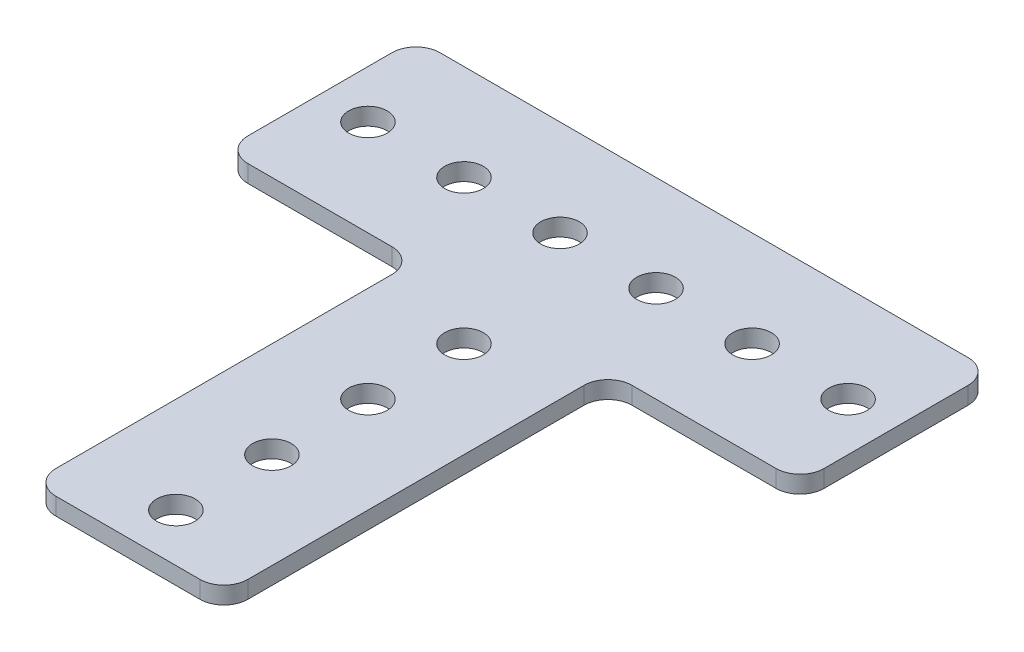
SolidWorks part; units mm, degrees
ref_plane "Front Plane" through (0, 0, 0) normal (0, 0, 1) x (1, 0, 0)
ref_plane "Top Plane" through (0, 0, 0) normal (0, 1, 0) x (1, 0, 0)
ref_plane "Right Plane" through (0, 0, 0) normal (1, 0, 0) x (0, 0, -1)
sketch "Sketch1" plane through (0, 0, 0) normal (0, 1, 0) x (1, 0, 0)
  line L0 (12.7, -12.7) -> (38.1, -12.7)
  line L1 (-38.1, 12.7) -> (38.1, 12.7)
  line L2 (-38.1, 12.7) -> (-38.1, -12.7)
  line L3 (-38.1, -12.7) -> (-12.7, -12.7)
  line L4 (38.1, 12.7) -> (38.1, -12.7)
  line L5 (-38.1, 12.7) -> (38.1, -12.7) construction
  line L6 (-38.1, -12.7) -> (38.1, 12.7) construction
  line L7 (12.7, -12.7) -> (12.7, -63.5)
  line L9 (-12.7, -63.5) -> (12.7, -63.5)
  line L10 (-12.7, -12.7) -> (-12.7, -63.5)
  point P0 (0, 0)
  point P8 (-12.7, 0)
  point P10 (12.7, 0)
  dimension "D1" = 25.4
  dimension "D2" = 76.2
  dimension "D3" = 25.4
  dimension "D6" = 25.4
  dimension "D4" = 50.8
  dimension "D5" = 25.4
extrude "Boss-Extrude1" add sketch "Sketch1" along normal mid plane 2.286
sketch "Sketch2" plane through (0, 1.143, 0) normal (0, 1, 0) x (1, 0, 0)
  line L0 (-38.1, 0) -> (38.1, 0) construction
  line L1 (-38.1, 12.7) -> (-38.1, -12.7) construction
  line L2 (38.1, -12.7) -> (38.1, 12.7) construction
  line L3 (0, 0) -> (0, -63.5) construction
  line L4 (-12.7, -63.5) -> (12.7, -63.5) construction
  line L5 (-12.7, -12.7) -> (12.7, -12.7) construction
  circle A0 centre (-31.75, 0) radius 2.5527
  circle A1 centre (-19.05, 0) radius 2.5527
  circle A2 centre (-6.35, 0) radius 2.5527
  circle A3 centre (6.35, 0) radius 2.5527
  circle A4 centre (19.05, 0) radius 2.5527
  circle A5 centre (0, -57.15) radius 2.5527
  circle A6 centre (31.75, 0) radius 2.5527
  circle A7 centre (0, -44.45) radius 2.5527
  circle A8 centre (0, -31.75) radius 2.5527
  circle A9 centre (0, -19.05) radius 2.5527
  dimension "D1" = 5.1054
  dimension "D4" = 5.1054
  dimension "D2" = 6.35
  dimension "D5" = 6.35
  dimension "D3" = 4
extrude "Cut-Extrude1" cut sketch "Sketch2" against normal through all
fillet "Fillet1" radius 3.175 8 edges at (38.1, 0, 12.7) (12.7, 0, 12.7) (-12.7, 0, 12.7) (-38.1, 0, 12.7) (-38.1, 0, -12.7) (38.1, 0, -12.7) (-12.7, 0, 63.5) (12.7, 0, 63.5)
